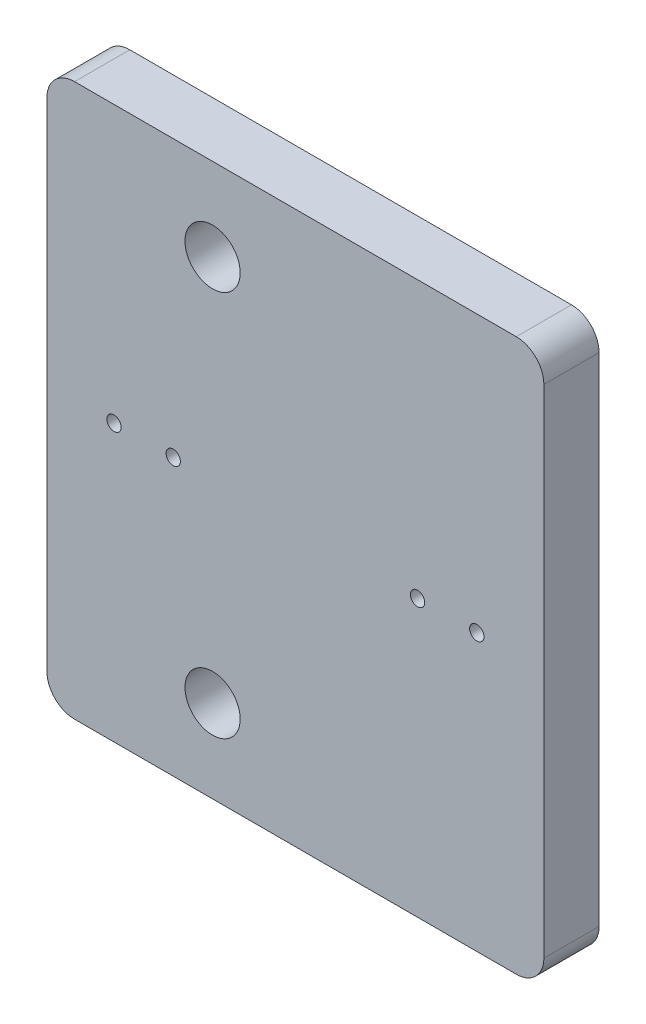
SolidWorks part; units mm, degrees
ref_plane "Front Plane" through (0, 0, 0) normal (0, 0, 1) x (1, 0, 0)
ref_plane "Top Plane" through (0, 0, 0) normal (0, 1, 0) x (1, 0, 0)
ref_plane "Right Plane" through (0, 0, 0) normal (1, 0, 0) x (0, 0, -1)
sketch "Sketch1" plane through (0, 0, 0) normal (0, 0, 1) x (1, 0, 0)
  line L0 (-57.15, 0) -> (57.15, 0) construction
  line L1 (-57.15, -63.5) -> (57.15, -63.5)
  line L2 (-57.15, -63.5) -> (-57.15, 63.5)
  line L3 (-57.15, 63.5) -> (57.15, 63.5)
  line L4 (57.15, -63.5) -> (57.15, 63.5)
  line L5 (-57.15, -63.5) -> (57.15, 63.5) construction
  line L6 (-57.15, 63.5) -> (57.15, -63.5) construction
  circle A0 centre (-41.7297, 0) radius 1.651
  circle A1 centre (-28.0975, 0) radius 1.651
  circle A2 centre (28.0975, 0) radius 1.651
  circle A3 centre (41.7297, 0) radius 1.651
  circle A4 centre (-19.05, 44.45) radius 6.35
  circle A5 centre (-19.05, -44.45) radius 6.35
  point P0 (0, 0)
  dimension "D3" = 15.4203
  dimension "D4" = 13.6322
  dimension "D5" = 13.6322
  dimension "D6" = 15.4203
  dimension "D7" = 3.302
  dimension "D8" = 12.7
  dimension "D9" = 38.1
  dimension "D10" = 19.05
  dimension "D11" = 12.7
  dimension "D12" = 38.1
  dimension "D13" = 19.05
  dimension "D1" = 127
  dimension "D2" = 114.3
extrude "Boss-Extrude1" add sketch "Sketch1" along normal blind 12.7
fillet "Fillet1" radius 6.35 4 edges at (-57.15, 63.5, 6.35) (-57.15, -63.5, 6.35) (57.15, -63.5, 6.35) (57.15, 63.5, 6.35)
